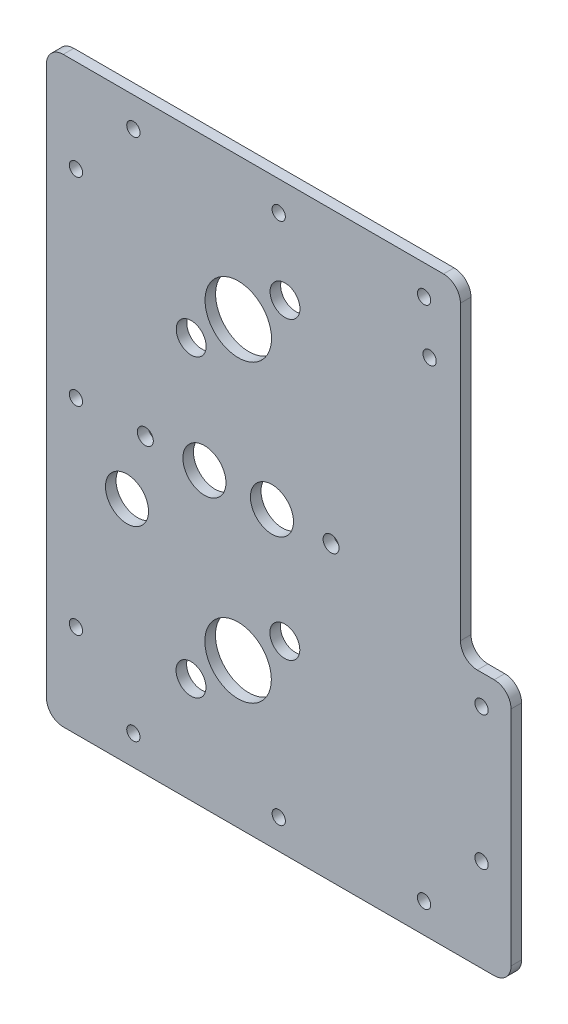
SolidWorks part; units mm, degrees
material "Alloy Steel (SS)"
ref_plane "X-Y Datum" through (0, 0, 0) normal (0, 0, 1) x (1, 0, 0)
ref_plane "X-Z Datum" through (0, 0, 0) normal (0, 1, 0) x (1, 0, 0)
ref_plane "Y-Z Datum" through (0, 0, 0) normal (1, 0, 0) x (0, 0, -1)
sketch "Sketch1" plane through (0, 0, 0) normal (0, 0, 1) x (1, 0, 0)
  line L0 (-11.0243, 39.9403) -> (-16.1043, 39.9403)
  line L1 (-140.6913, 138.0723) -> (-26.2643, 138.0723)
  line L2 (-145.7713, 132.9923) -> (-145.7713, -32.1077)
  line L3 (-140.6913, -37.1877) -> (-11.0243, -37.1877)
  line L4 (-5.9443, 34.8603) -> (-5.9443, -32.1077)
  line L5 (-21.1843, 45.0203) -> (-21.1843, 132.9923)
  arc A0 (-145.7713, -32.1077) -> (-140.6913, -37.1877) centre (-140.6913, -32.1077) ccw
  arc A1 (-11.0243, -37.1877) -> (-5.9443, -32.1077) centre (-11.0243, -32.1077) ccw
  arc A2 (-11.0243, 39.9403) -> (-5.9443, 34.8603) centre (-11.0243, 34.8603) cw
  arc A3 (-16.1043, 39.9403) -> (-21.1843, 45.0203) centre (-16.1043, 45.0203) cw
  arc A4 (-21.1843, 132.9923) -> (-26.2643, 138.0723) centre (-26.2643, 132.9923) ccw
  arc A5 (-140.6913, 138.0723) -> (-145.7713, 132.9923) centre (-140.6913, 132.9923) ccw
  circle A6 centre (-98.216, 50.8911) radius 6.477
  circle A7 centre (-77.896, 50.9089) radius 6.477
  circle A8 centre (-60.1036, 50.8756) radius 2.4
  circle A9 centre (-115.996, 50.8756) radius 2.4
  circle A10 centre (-121.5143, 31.8208) radius 6.477
  circle A11 centre (-88.0294, 95.3501) radius 10
  circle A12 centre (-102.2012, 83.4585) radius 4.5
  circle A13 centre (-73.9636, 107.3675) radius 4.5
  circle A14 centre (-88.0827, 6.45) radius 10
  circle A15 centre (-102.2545, -5.4416) radius 4.5
  circle A16 centre (-74.017, 18.4674) radius 4.5
  circle A17 centre (-119.5956, 129.1823) radius 2
  circle A18 centre (-75.8578, 129.1823) radius 2
  circle A19 centre (-32.12, 129.1823) radius 2
  circle A20 centre (-136.8813, 110.1323) radius 2
  circle A21 centre (-30.4553, 114.1963) radius 2
  circle A22 centre (-136.8813, 50.4423) radius 2
  circle A23 centre (-136.8813, -9.2477) radius 2
  circle A24 centre (-119.5956, -28.2977) radius 2
  circle A25 centre (-75.8578, -28.2977) radius 2
  circle A26 centre (-32.12, -28.2977) radius 2
  circle A27 centre (-14.8343, -9.2477) radius 2
  circle A28 centre (-14.8343, 31.0503) radius 2
  point P40 (-88.0294, 95.3501)
  point P41 (-88.0827, 6.45)
  dimension "D1" = 5.08
extrude "Boss-Extrude1" add sketch "Sketch1" along normal blind 3.175
